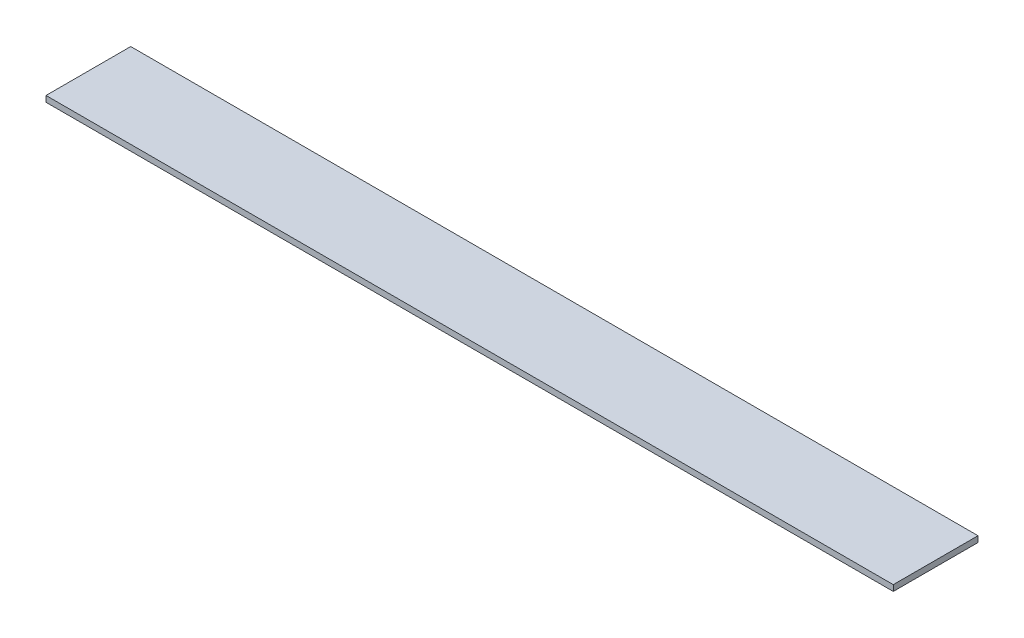
SolidWorks part; units mm, degrees
ref_plane "Front Plane" through (0, 0, 0) normal (0, 0, 1) x (1, 0, 0)
ref_plane "Top Plane" through (0, 0, 0) normal (0, 1, 0) x (1, 0, 0)
ref_plane "Right Plane" through (0, 0, 0) normal (1, 0, 0) x (0, 0, -1)
sketch "Sketch1" plane through (0, 0, 0) normal (0, 1, 0) x (1, 0, 0)
  line L1 (-50, -5) -> (50, -5)
  line L2 (-50, -5) -> (-50, 5)
  line L3 (-50, 5) -> (50, 5)
  line L4 (50, -5) -> (50, 5)
  line L5 (-50, -5) -> (50, 5) construction
  line L6 (-50, 5) -> (50, -5) construction
  point P0 (0, 0)
  dimension "D1" = 10
  dimension "D2" = 100
extrude "Boss-Extrude1" add sketch "Sketch1" along normal blind 0.7
